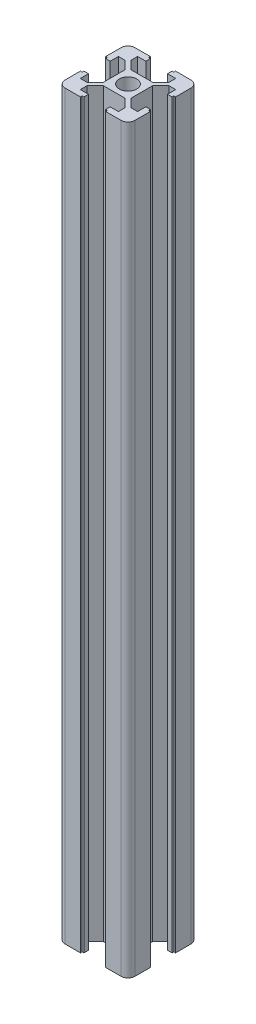
SolidWorks part; units mm, degrees
ref_plane "前视基准面" through (0, 0, 0) normal (0, 0, 1) x (1, 0, 0)
ref_plane "上视基准面" through (0, 0, 0) normal (0, 1, 0) x (1, 0, 0)
ref_plane "右视基准面" through (0, 0, 0) normal (1, 0, 0) x (0, 0, -1)
sketch "草图1" plane through (0, 0, 0) normal (0, 1, 0) x (1, 0, 0)
  line L0 (-6.2985, -5.45) -> (-3.9485, -3.1)
  line L1 (-5.45, -6.2985) -> (-3.1, -3.9485)
  line L2 (-6.2985, -5.45) -> (-8.2, -5.45)
  line L3 (-8.2, -5.45) -> (-8.2, -3.1)
  line L4 (-8.2, -3.1) -> (-10, -3.1)
  line L5 (-10, -3.1) -> (-10, -8)
  line L6 (-8, -10) -> (-3.1, -10)
  line L7 (-5.45, -6.2985) -> (-5.45, -8.2)
  line L8 (-5.45, -8.2) -> (-3.1, -8.2)
  line L9 (-3.1, -8.2) -> (-3.1, -10)
  line L10 (-3.9485, 0) -> (-3.9485, -3.1)
  line L11 (-3.1, -3.9485) -> (0, -3.9485)
  line L12 (-10, -3.6) -> (-9.5, -3.6)
  line L13 (-9.5, -3.6) -> (-9.5, -3.1)
  line L14 (-3.6, -10) -> (-3.6, -9.5)
  line L15 (-3.6, -9.5) -> (-3.1, -9.5)
  line L16 (-3.9485, 0) -> (-2.5, 0) construction
  line L17 (0, -2.5) -> (0, -3.9485) construction
  line L18 (-5.45, 6.2985) -> (-3.1, 3.9485)
  line L19 (-6.2985, 5.45) -> (-3.9485, 3.1)
  line L20 (-5.45, 6.2985) -> (-5.45, 8.2)
  line L21 (-5.45, 8.2) -> (-3.1, 8.2)
  line L22 (-3.1, 8.2) -> (-3.1, 10)
  line L23 (-3.1, 10) -> (-8, 10)
  line L24 (-10, 8) -> (-10, 3.1)
  line L25 (-6.2985, 5.45) -> (-8.2, 5.45)
  line L26 (-8.2, 5.45) -> (-8.2, 3.1)
  line L27 (-8.2, 3.1) -> (-10, 3.1)
  line L28 (-3.1, 3.9485) -> (0, 3.9485)
  line L29 (-3.9485, 3.1) -> (-3.9485, 0)
  line L30 (-3.6, 10) -> (-3.6, 9.5)
  line L31 (-3.6, 9.5) -> (-3.1, 9.5)
  line L32 (-10, 3.6) -> (-9.5, 3.6)
  line L33 (-9.5, 3.6) -> (-9.5, 3.1)
  line L34 (0, 3.9485) -> (0, 2.5) construction
  line L35 (-2.5, 0) -> (-3.9485, 0) construction
  line L36 (6.2985, 5.45) -> (3.9485, 3.1)
  line L37 (5.45, 6.2985) -> (3.1, 3.9485)
  line L38 (6.2985, 5.45) -> (8.2, 5.45)
  line L39 (8.2, 5.45) -> (8.2, 3.1)
  line L40 (8.2, 3.1) -> (10, 3.1)
  line L41 (10, 3.1) -> (10, 8)
  line L42 (8, 10) -> (3.1, 10)
  line L43 (5.45, 6.2985) -> (5.45, 8.2)
  line L44 (5.45, 8.2) -> (3.1, 8.2)
  line L45 (3.1, 8.2) -> (3.1, 10)
  line L46 (3.9485, 0) -> (3.9485, 3.1)
  line L47 (3.1, 3.9485) -> (0, 3.9485)
  line L48 (10, 3.6) -> (9.5, 3.6)
  line L49 (9.5, 3.6) -> (9.5, 3.1)
  line L50 (3.6, 10) -> (3.6, 9.5)
  line L51 (3.6, 9.5) -> (3.1, 9.5)
  line L52 (3.9485, 0) -> (2.5, 0) construction
  line L53 (0, 2.5) -> (0, 3.9485) construction
  line L54 (5.45, -6.2985) -> (3.1, -3.9485)
  line L55 (6.2985, -5.45) -> (3.9485, -3.1)
  line L56 (5.45, -6.2985) -> (5.45, -8.2)
  line L57 (5.45, -8.2) -> (3.1, -8.2)
  line L58 (3.1, -8.2) -> (3.1, -10)
  line L59 (3.1, -10) -> (8, -10)
  line L60 (10, -8) -> (10, -3.1)
  line L61 (6.2985, -5.45) -> (8.2, -5.45)
  line L62 (8.2, -5.45) -> (8.2, -3.1)
  line L63 (8.2, -3.1) -> (10, -3.1)
  line L64 (0, -3.9485) -> (3.1, -3.9485)
  line L65 (3.9485, -3.1) -> (3.9485, 0)
  line L66 (3.6, -10) -> (3.6, -9.5)
  line L67 (3.6, -9.5) -> (3.1, -9.5)
  line L68 (10, -3.6) -> (9.5, -3.6)
  line L69 (9.5, -3.6) -> (9.5, -3.1)
  line L70 (0, -3.9485) -> (0, -2.5) construction
  line L71 (2.5, 0) -> (3.9485, 0) construction
  line L72 (0, 3.9485) -> (-3.1, 3.9485) [skipped]
  circle A0 centre (0, 0) radius 2.5
  arc A1 (-10, -8) -> (-8, -10) centre (-8, -8) ccw
  arc A3 (-8, 10) -> (-10, 8) centre (-8, 8) ccw
  arc A5 (10, 8) -> (8, 10) centre (8, 8) ccw
  arc A7 (8, -10) -> (10, -8) centre (8, -8) ccw
  point P25 (-10, -10)
  point P98 (0, 0)
  dimension "D9" = 2
  dimension "D15" = 5
  dimension "D2" = 1.2
  dimension "D4" = 5.45
  dimension "D5" = 1.8
  dimension "D6" = 3.1
  dimension "D7" = 135
  dimension "D10" = 0.5
  dimension "D11" = 0.5
  dimension "D12" = 0.5
  dimension "D13" = 0.5
  dimension "D14" = 4
extrude "凸台-拉伸1" add sketch "草图1" along normal blind 212.04 contours L59 A7 L60 L68 L69 L63 L62 L61 L55 L65 L46 L36 L38 L39 L40 L49 L48 L41 A5 L42 L50 L51 L45 L44 L43 L37 L47 L28 L18 L20 L21 L22 L31 L30 L23 A3 L24 L32 L33 L27 L26 L25 L19 L29 L10 L0 L2 L3 L4 L13 L12
